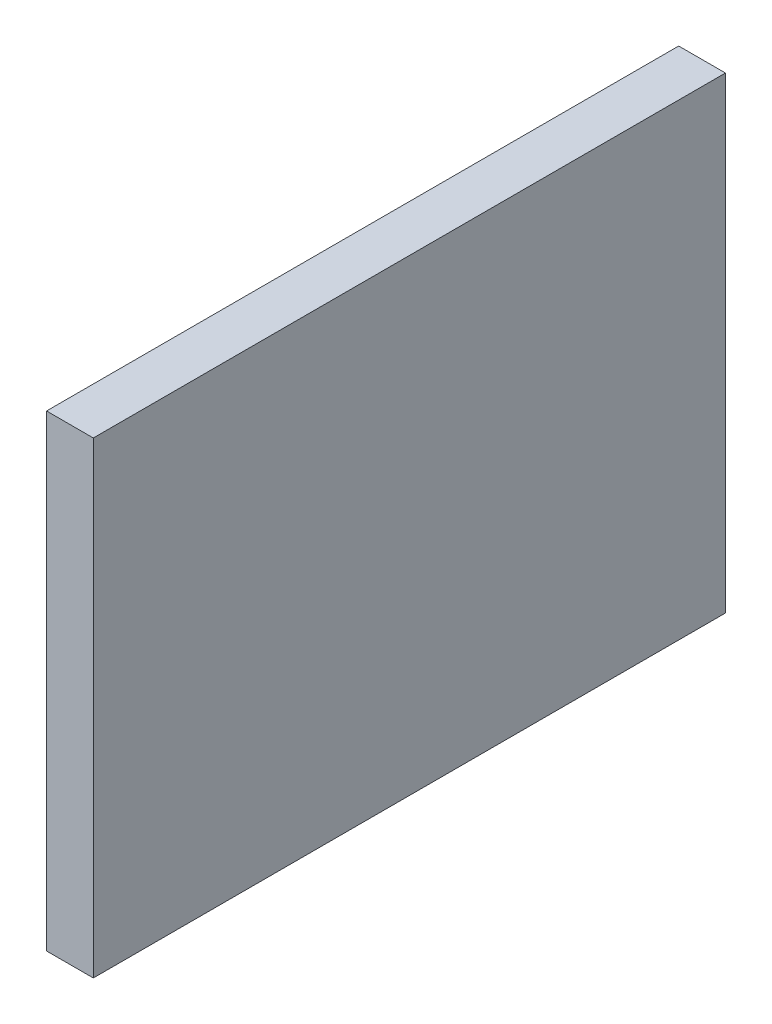
SolidWorks part; units mm, degrees
material "Acrylic (Medium-high impact)"
ref_plane "Front Plane" through (0, 0, 0) normal (0, 0, 1) x (1, 0, 0)
ref_plane "Top Plane" through (0, 0, 0) normal (0, 1, 0) x (1, 0, 0)
ref_plane "Right Plane" through (0, 0, 0) normal (1, 0, 0) x (0, 0, -1)
sketch "Sketch1" plane through (0, 0, 0) normal (1, 0, 0) x (0, 0, -1)
  line L1 (0, 0) -> (40.55, 0)
  line L2 (0, 0) -> (0, 30)
  line L3 (0, 30) -> (40.55, 30)
  line L4 (40.55, 0) -> (40.55, 30)
  dimension "D1" = 30
  dimension "D2" = 40.55
extrude "Boss-Extrude1" add sketch "Sketch1" along normal blind 3
